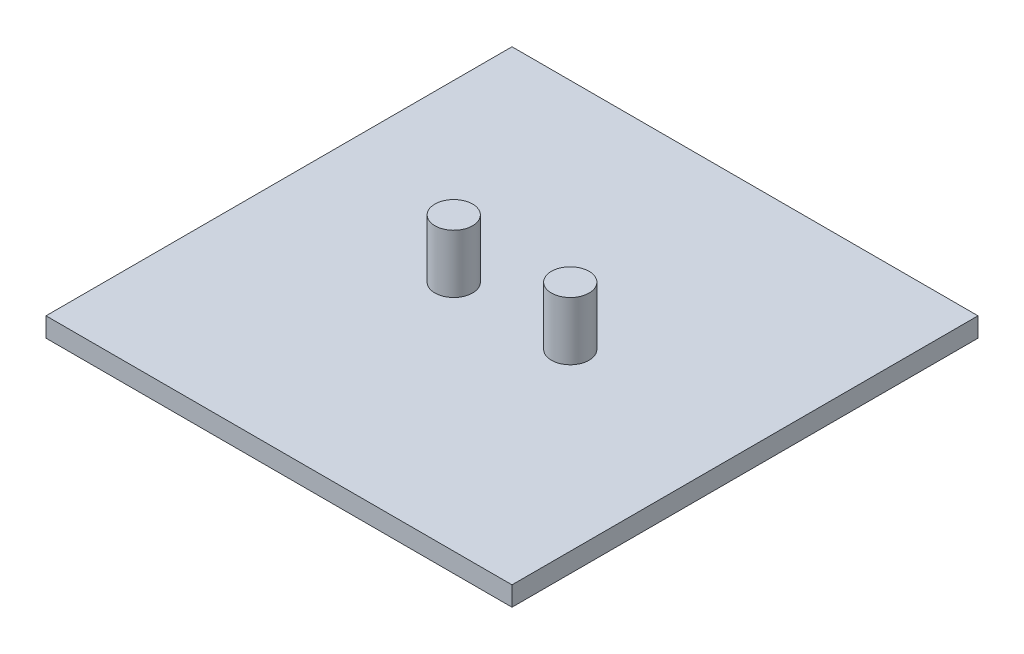
SolidWorks part; units mm, degrees
ref_plane "Front Plane" through (0, 0, 0) normal (0, 0, 1) x (1, 0, 0)
ref_plane "Top Plane" through (0, 0, 0) normal (0, 1, 0) x (1, 0, 0)
ref_plane "Right Plane" through (0, 0, 0) normal (1, 0, 0) x (0, 0, -1)
sketch "Sketch1" plane through (0, 0, 0) normal (0, 1, 0) x (1, 0, 0)
  line L0 (-7.5, 0) -> (7.5, 0) construction
  circle A0 centre (-7.5, 0) radius 2.425
  circle A1 centre (7.5, 0) radius 2.425
  point P4 (0, 0)
  dimension "D2" = 4.85
  dimension "D1" = 15
extrude "Boss-Extrude1" add sketch "Sketch1" along normal blind 7.5
sketch "Sketch2" plane through (0, 0, 0) normal (0, 1, 0) x (1, 0, 0)
  line L1 (-30, 30) -> (30, 30)
  line L2 (-30, 30) -> (-30, -30)
  line L3 (-30, -30) -> (30, -30)
  line L4 (30, 30) -> (30, -30)
  line L5 (-30, 30) -> (30, -30) construction
  line L6 (-30, -30) -> (30, 30) construction
  point P0 (0, 0)
  dimension "D1" = 60
extrude "Boss-Extrude2" add sketch "Sketch2" against normal blind 2.5
fillet "Fillet1" [suppressed] radius 4
fillet "Fillet2" [suppressed] radius 2
